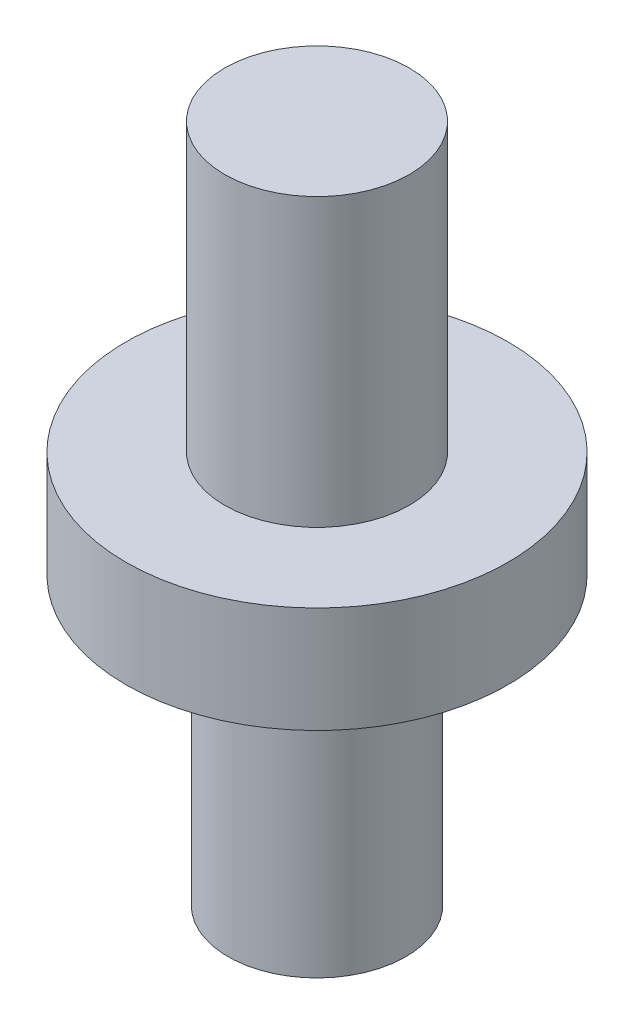
SolidWorks part; units mm, degrees
ref_plane "Front Plane" through (0, 0, 0) normal (0, 0, 1) x (1, 0, 0)
ref_plane "Top Plane" through (0, 0, 0) normal (0, 1, 0) x (1, 0, 0)
ref_plane "Right Plane" through (0, 0, 0) normal (1, 0, 0) x (0, 0, -1)
sketch "Sketch2" plane through (0, 0, 0) normal (0, 1, 0) x (1, 0, 0)
  circle A0 centre (0, 0) radius 2.175
  point P3 (0, 0)
  dimension "D1" = 4.35
extrude "Boss-Extrude2" add sketch "Sketch2" along normal blind 8
sketch "Sketch5" plane through (0, 0, 0) normal (0, -1, 0) x (-1, 0, 0)
  circle A0 centre (0, 0) radius 2.095
  circle A1 centre (0, 0) radius 2.175 construction
  dimension "D1" = 4.19
extrude "Boss-Extrude3" add sketch "Sketch5" along normal blind 8
ref_plane "Plane4" through (0, 0, 0) normal (0, -1, 0) x (-1, 0, 0)
sketch "Sketch7" plane through (0, 0, 0) normal (0, -1, 0) x (-1, 0, 0)
  circle A0 centre (0, 0) radius 4.5
  dimension "D1" = 9
extrude "Boss-Extrude4" add sketch "Sketch7" along normal mid plane 2.5
